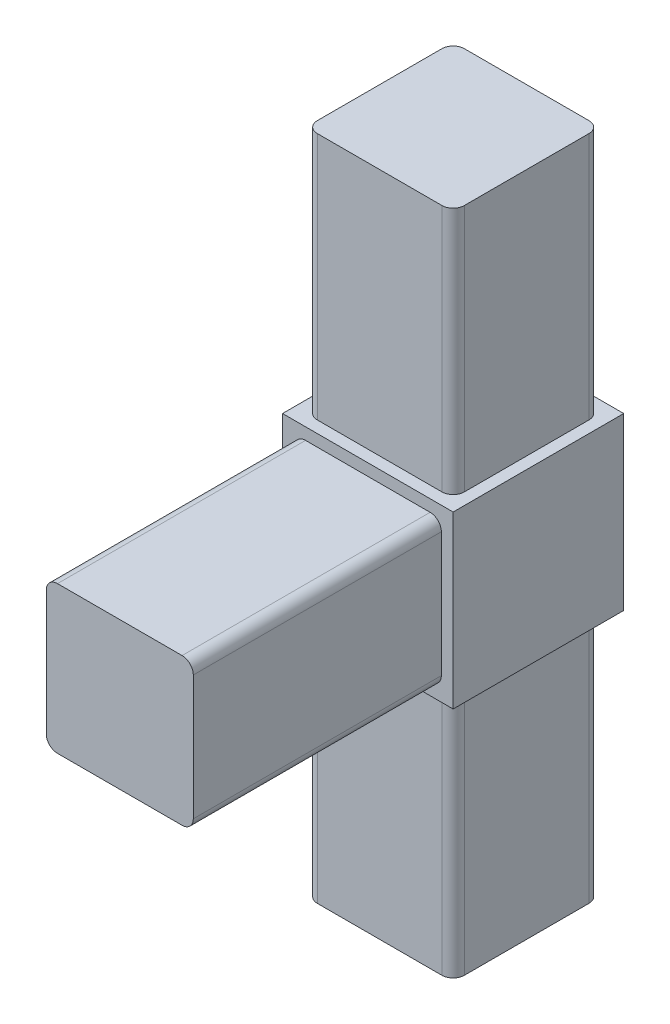
SolidWorks part; units mm, degrees
ref_plane "Front Plane" through (0, 0, 0) normal (0, 0, 1) x (1, 0, 0)
ref_plane "Top Plane" through (0, 0, 0) normal (0, 1, 0) x (1, 0, 0)
ref_plane "Right Plane" through (0, 0, 0) normal (1, 0, 0) x (0, 0, -1)
sketch "Sketch1" plane through (0, 0, 0) normal (0, 1, 0) x (1, 0, 0)
  line L1 (-8.3185, 8.3185) -> (8.3185, 8.3185)
  line L2 (-8.3185, 8.3185) -> (-8.3185, -8.3185)
  line L3 (-8.3185, -8.3185) -> (8.3185, -8.3185)
  line L4 (8.3185, 8.3185) -> (8.3185, -8.3185)
  line L5 (-8.3185, 8.3185) -> (8.3185, -8.3185) construction
  line L6 (-8.3185, -8.3185) -> (8.3185, 8.3185) construction
  point P0 (0, 0)
  dimension "D1" = 16.637
extrude "Boss-Extrude1" add sketch "Sketch1" along normal blind 28.067
sketch "Sketch2" plane through (0, 28.067, 0) normal (0, 1, 0) x (1, 0, 0)
  line L1 (-9.652, -9.652) -> (9.652, -9.652)
  line L2 (-9.652, -9.652) -> (-9.652, 9.652)
  line L3 (-9.652, 9.652) -> (9.652, 9.652)
  line L4 (9.652, -9.652) -> (9.652, 9.652)
  line L5 (-9.652, -9.652) -> (9.652, 9.652) construction
  line L6 (-9.652, 9.652) -> (9.652, -9.652) construction
  point P0 (0, 0)
  dimension "D1" = 19.304
  dimension "D2" = 19.304
extrude "Boss-Extrude2" add sketch "Sketch2" along normal blind 19.304
sketch "Sketch3" plane through (0, 0, 9.652) normal (0, 0, 1) x (1, 0, 0)
  line L0 (-9.652, 47.371) -> (9.652, 28.067) construction
  line L2 (-8.3185, 29.4005) -> (8.3185, 29.4005)
  line L3 (-8.3185, 29.4005) -> (-8.3185, 46.0375)
  line L4 (-8.3185, 46.0375) -> (8.3185, 46.0375)
  line L5 (8.3185, 29.4005) -> (8.3185, 46.0375)
  line L6 (-8.3185, 29.4005) -> (8.3185, 46.0375) construction
  line L7 (-8.3185, 46.0375) -> (8.3185, 29.4005) construction
  point P4 (0, 37.719)
  dimension "D1" = 16.637
extrude "Boss-Extrude3" add sketch "Sketch3" along normal blind 28.067
sketch "Sketch5" plane through (0, 47.371, 0) normal (0, 1, 0) x (1, 0, 0)
  line L0 (-9.652, 9.652) -> (9.652, -9.652) construction
  line L2 (-8.3185, -8.3185) -> (8.3185, -8.3185)
  line L3 (-8.3185, -8.3185) -> (-8.3185, 8.3185)
  line L4 (-8.3185, 8.3185) -> (8.3185, 8.3185)
  line L5 (8.3185, -8.3185) -> (8.3185, 8.3185)
  line L6 (-8.3185, -8.3185) -> (8.3185, 8.3185) construction
  line L7 (-8.3185, 8.3185) -> (8.3185, -8.3185) construction
  point P4 (0, 0)
  dimension "D1" = 16.637
extrude "Boss-Extrude4" add sketch "Sketch5" along normal blind 28.067
fillet "Fillet1" radius 1.27 12 edges at (-8.3185, 14.0335, 8.3185) (8.3185, 14.0335, 8.3185) (-8.3185, 14.0335, -8.3185) (8.3185, 14.0335, -8.3185) (-8.3185, 29.4005, 23.6855) (-8.3185, 46.0375, 23.6855) (8.3185, 29.4005, 23.6855) (8.3185, 46.0375, 23.6855) (-8.3185, 61.4045, 8.3185) (8.3185, 61.4045, 8.3185) (-8.3185, 61.4045, -8.3185) (8.3185, 61.4045, -8.3185)
